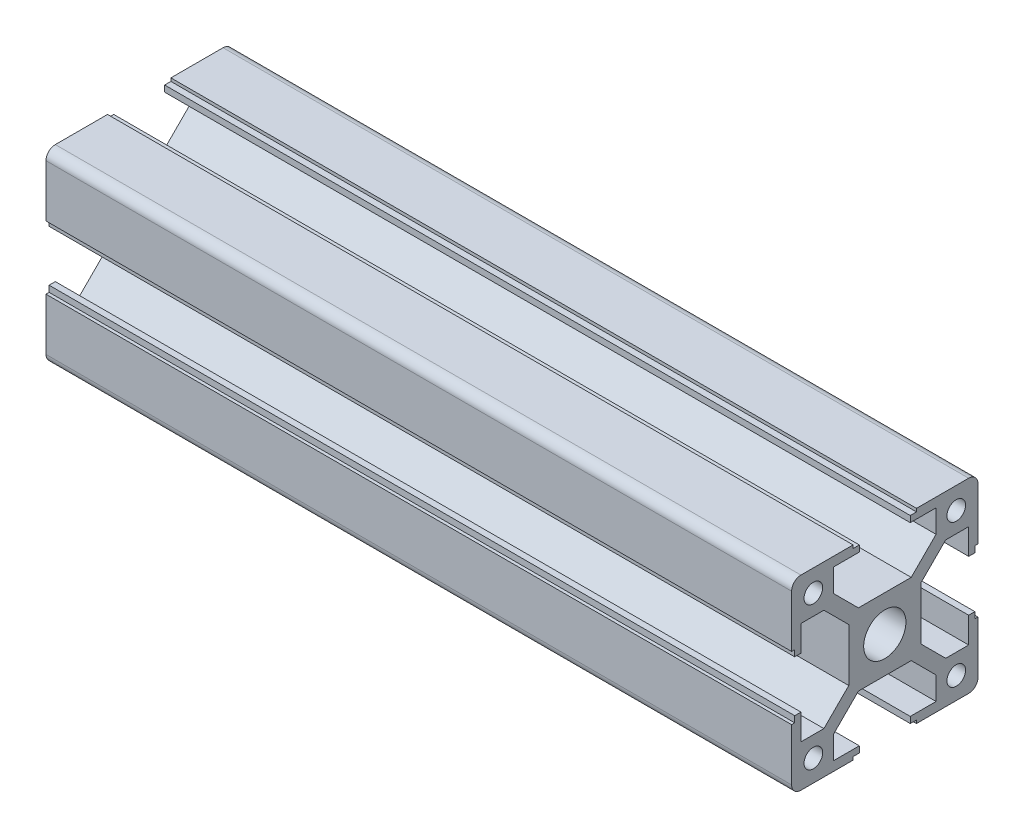
SolidWorks part; units mm, degrees
ref_plane "前视基准面" through (0, 0, 0) normal (0, 0, 1) x (1, 0, 0)
ref_plane "上视基准面" through (0, 0, 0) normal (0, 1, 0) x (1, 0, 0)
ref_plane "右视基准面" through (0, 0, 0) normal (1, 0, 0) x (0, 0, -1)
sketch "草图1" plane through (0, 0, 0) normal (0, 1, 0) x (1, 0, 0)
  line L0 (0, 0) -> (120, 0)
  dimension "D1" = 120
other "铝型材 30X 30G X R1.5(1)"
ref_plane "基准面1" through (0, 0, 0) normal (1, 0, 0) x (0, 0, -1)
sketch "Sketch12" plane through (0, 0, 0) normal (1, 0, 0) x (0, 0, -1)
  line L0 (-5.1, 15) -> (-5.1, 14.5)
  line L1 (-5.1, 14.5) -> (-4.1, 14.5)
  line L2 (-4.1, 14.5) -> (-4.1, 13.5)
  line L3 (-4.1, 13.5) -> (-8.25, 13.5)
  line L4 (-13.5, -15) -> (-5.1, -15)
  line L5 (-15, -13.5) -> (-15, -5.1)
  line L6 (13.5, 15) -> (5.1, 15)
  line L7 (15, 13.5) -> (15, 5.1)
  line L8 (0, 14.8756) -> (0, 0) construction
  line L9 (0, 0) -> (14.1675, 0) construction
  line L10 (-8.25, 13.5) -> (-8.25, 9.8)
  line L11 (-8.25, 9.8) -> (-4.25, 5.8)
  line L12 (-4.25, 5.8) -> (4.25, 5.8)
  line L13 (8.25, 9.8) -> (4.25, 5.8)
  line L14 (8.25, 13.5) -> (8.25, 9.8)
  line L15 (4.1, 13.5) -> (8.25, 13.5)
  line L16 (4.1, 14.5) -> (4.1, 13.5)
  line L17 (5.1, 14.5) -> (4.1, 14.5)
  line L18 (5.1, 15) -> (5.1, 14.5)
  line L19 (-5.1, 15) -> (-13.5, 15)
  line L20 (15, 5.1) -> (14.5, 5.1)
  line L21 (14.5, 5.1) -> (14.5, 4.1)
  line L22 (14.5, 4.1) -> (13.5, 4.1)
  line L23 (13.5, 4.1) -> (13.5, 8.25)
  line L24 (13.5, 8.25) -> (9.8, 8.25)
  line L25 (9.8, 8.25) -> (5.8, 4.25)
  line L26 (5.8, 4.25) -> (5.8, -4.25)
  line L27 (9.8, -8.25) -> (5.8, -4.25)
  line L28 (13.5, -8.25) -> (9.8, -8.25)
  line L29 (13.5, -4.1) -> (13.5, -8.25)
  line L30 (14.5, -4.1) -> (13.5, -4.1)
  line L31 (14.5, -5.1) -> (14.5, -4.1)
  line L32 (15, -5.1) -> (14.5, -5.1)
  line L33 (5.1, -15) -> (5.1, -14.5)
  line L34 (5.1, -14.5) -> (4.1, -14.5)
  line L35 (4.1, -14.5) -> (4.1, -13.5)
  line L36 (4.1, -13.5) -> (8.25, -13.5)
  line L37 (8.25, -13.5) -> (8.25, -9.8)
  line L38 (8.25, -9.8) -> (4.25, -5.8)
  line L39 (4.25, -5.8) -> (-4.25, -5.8)
  line L40 (-8.25, -9.8) -> (-4.25, -5.8)
  line L41 (-8.25, -13.5) -> (-8.25, -9.8)
  line L42 (-4.1, -13.5) -> (-8.25, -13.5)
  line L43 (-4.1, -14.5) -> (-4.1, -13.5)
  line L44 (-5.1, -14.5) -> (-4.1, -14.5)
  line L45 (-5.1, -15) -> (-5.1, -14.5)
  line L46 (-15, -5.1) -> (-14.5, -5.1)
  line L47 (-14.5, -5.1) -> (-14.5, -4.1)
  line L48 (-14.5, -4.1) -> (-13.5, -4.1)
  line L49 (-13.5, -4.1) -> (-13.5, -8.25)
  line L50 (-13.5, -8.25) -> (-9.8, -8.25)
  line L51 (-9.8, -8.25) -> (-5.8, -4.25)
  line L52 (-5.8, -4.25) -> (-5.8, 4.25)
  line L53 (-9.8, 8.25) -> (-5.8, 4.25)
  line L54 (-13.5, 8.25) -> (-9.8, 8.25)
  line L55 (-13.5, 4.1) -> (-13.5, 8.25)
  line L56 (-14.5, 4.1) -> (-13.5, 4.1)
  line L57 (-14.5, 5.1) -> (-14.5, 4.1)
  line L58 (-15, 5.1) -> (-14.5, 5.1)
  line L59 (5.1, -15) -> (13.5, -15)
  line L60 (-15, 5.1) -> (-15, 13.5)
  line L61 (15, -5.1) -> (15, -13.5)
  circle A0 centre (0, 0) radius 3.4
  arc A1 (-15, 13.5) -> (-13.5, 15) centre (-13.5, 13.5) cw
  arc A2 (15, 13.5) -> (13.5, 15) centre (13.5, 13.5) ccw
  arc A3 (-13.5, -15) -> (-15, -13.5) centre (-13.5, -13.5) cw
  arc A4 (13.5, -15) -> (15, -13.5) centre (13.5, -13.5) ccw
  circle A5 centre (-11.5, 11.5) radius 1.5
  circle A6 centre (11.5, 11.5) radius 1.5
  circle A7 centre (-11.5, -11.5) radius 1.5
  circle A8 centre (11.5, -11.5) radius 1.5
  point P0 (-10, 0)
  point P1 (10, 0)
  point P2 (0, 10)
  point P3 (0, -10)
  point P4 (0, 0)
  point P5 (-15, -15)
  point P6 (15, -15)
  point P7 (15, 15)
  point P8 (-15, 15)
  point P36 (-15, 15)
  point P39 (15, 15)
  point P92 (0, 0)
  dimension "D1" = 16.5
  dimension "D2" = 30
  dimension "D3" = 8.2
  dimension "D4" = 10.2
  dimension "D5" = 9.2
  dimension "D6" = 6.8
  dimension "D7" = 1.5
  dimension "D8" = 45
  dimension "D12" = 3
  dimension "D13" = 23
  dimension "D14" = 23
  dimension "D9" = 0.5
  dimension "D10" = 1
  dimension "D11" = 8.5
